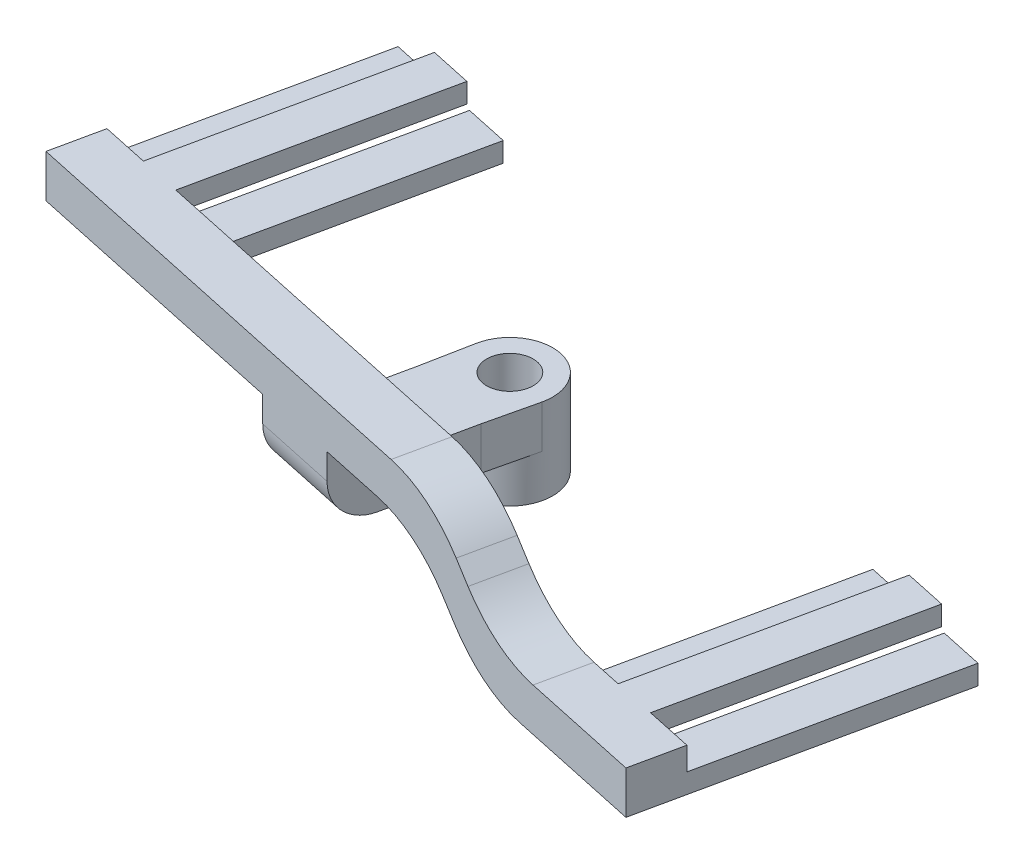
SolidWorks part; units mm, degrees
ref_plane "Front Plane" through (0, 0, 0) normal (0, 0, 1) x (1, 0, 0)
ref_plane "Top Plane" through (0, 0, 0) normal (0, 1, 0) x (1, 0, 0)
ref_plane "Right Plane" through (0, 0, 0) normal (1, 0, 0) x (0, 0, -1)
sketch "Sketch1" plane through (0, 0, 0) normal (0, 1, 0) x (1, 0, 0)
  circle A0 centre (0, 0) radius 3.175
  dimension "D1" = 6.35
extrude "Boss-Extrude1" add sketch "Sketch1" along normal blind 8.89
hole_wizard "#4 Clearance Hole1" positions "Sketch3" profile "Sketch2" hole size "#4" standard "ANSI Inch" end condition through all
sketch "Sketch3" plane through (0, 8.89, 0) normal (0, 1, 0) x (1, 0, 0)
  point P0 (0, 0)
sketch "Sketch2" plane through (0, 8.89, 0) normal (1, 0, 0) x (0, 0, 1)
  line L0 (0, 0) -> (0, 8.89)
  line L1 (0, 8.89) -> (1.7272, 8.89)
  line L2 (1.7272, 8.89) -> (1.7272, 0)
  line L5 (1.7272, 0) -> (0, 0)
  line L11 (0, -6.35) -> (0, 107.95) construction
  dimension "Thru Hole Dia." = 3.4544
  dimension "Thru Hole Depth" = 8.89
sketch "Sketch4" plane through (0, 8.89, 0) normal (0, 1, 0) x (1, 0, 0)
  line L0 (-32.7152, 14.478) -> (-32.7152, -1.524) construction
  line L1 (-1.7272, 1.7272) -> (-1.7272, -1.7272) construction
  line L2 (1.7272, 1.7272) -> (1.7272, -1.7272) construction
  line L3 (-1.7272, -1.7272) -> (1.7272, -1.7272) construction
  line L4 (-1.7272, 1.7272) -> (1.7272, 1.7272) construction
  line L5 (47.1932, -2.667) -> (47.1932, -18.669) construction
  line L6 (-32.7152, 14.478) -> (47.1932, -2.667) construction
  line L7 (47.1932, -18.669) -> (-32.7152, -1.524) construction
  circle A1 centre (0, 0) radius 1.7272 construction
  dimension "D2" = 45.466
  dimension "D1" = 30.988
  dimension "D3" = 16.002
  dimension "D4" = 16.002
  dimension "D5" = 2.667
  dimension "D6" = 1.524
sketch "Sketch5" plane through (0, 8.89, 0) normal (0, 1, 0) x (1, 0, 0)
  line L0 (8.5844, -15.5808) -> (-26.3256, -8.0906)
  line L1 (47.1932, -18.669) -> (-32.7152, -1.524) construction
  line L2 (-3.175, 0) -> (-3.175, -9.161)
  line L3 (-26.3256, -8.0906) -> (-21.7112, 13.4159)
  line L4 (3.175, 0) -> (3.175, -10.5234)
  line L5 (9.3837, -11.8556) -> (8.5844, -15.5808)
  line L7 (-15.5924, -6.4967) -> (-3.175, -9.161)
  line L8 (-21.7112, 13.4159) -> (-11.7773, 11.2845)
  line L9 (-11.7773, 11.2845) -> (-15.5924, -6.4967)
  line L10 (-32.7152, 14.478) -> (47.1932, -2.667) construction
  line L14 (9.3837, -11.8556) -> (3.175, -10.5234)
  circle A0 centre (0, 0) radius 3.175 construction
  arc A1 (-3.175, 0) -> (3.175, 0) centre (0, 0) ccw
  dimension "D1" = 3.81
  dimension "D2" = 1.27
  dimension "D3" = 12.7
  dimension "D4" = 10.16
  dimension "D5" = 1.27
  dimension "D8" = 6.35
extrude "Boss-Extrude2" add sketch "Sketch5" against normal blind 3.175
sketch "Sketch11" plane through (-2.8181, 0, 13.1343) normal (-0.2098, 0, 0.9777) x (0.9777, 0, 0.2098)
  line L0 (11.662, 8.89) -> (12.9771, 8.89)
  line L1 (-35.0245, 8.89) -> (46.7025, 8.89) construction
  line L2 (18.012, -0.635) -> (11.662, 5.715)
  line L3 (11.662, 5.715) -> (11.662, 8.89) construction
  line L4 (11.662, 8.89) -> (11.662, 5.715)
  line L5 (19.3271, 2.54) -> (21.822, 2.54)
  line L6 (12.9771, 8.89) -> (19.3271, 2.54)
  line L7 (18.012, -0.635) -> (21.822, -0.635)
  line L8 (11.662, 5.715) -> (-24.0425, 5.715) construction
  line L9 (21.822, 2.54) -> (21.822, -0.635)
  dimension "D1" = 3.175
  dimension "D2" = 6.35
  dimension "D3" = 3.175
  dimension "D4" = 45
  dimension "D5" = 3.81
extrude "Boss-Extrude3" add sketch "Sketch11" against normal up to surface (3.81 mm away) up to face at (6.2793, 7.3025, 11.1895)
sketch "Sketch12" plane through (0, 8.89, 0) normal (0, 1, 0) x (1, 0, 0)
  line L0 (18.5183, -17.7122) -> (23.1327, 3.7943)
  line L1 (23.1327, 3.7943) -> (33.0666, 1.6629)
  line L2 (33.0666, 1.6629) -> (28.4523, -19.8436)
  line L3 (28.4523, -19.8436) -> (18.5183, -17.7122)
  line L4 (-32.7152, 14.478) -> (47.1932, -2.667) construction
  dimension "D1" = 10.16
  dimension "D2" = 1.27
extrude "Boss-Extrude4" add sketch "Sketch12" against normal up to vertex from vertex
sketch "Sketch6" plane through (1.7963, 0, -8.3722) normal (0.2098, 0, -0.9777) x (-0.9777, 0, -0.2098)
  line L0 (24.0425, 7.3025) -> (13.8825, 7.3025) construction
  line L1 (-21.822, 0.9525) -> (-31.982, 0.9525) construction
  line L2 (13.8825, 5.715) -> (13.8825, 8.89) construction
  line L3 (17.2692, 5.715) -> (17.2692, 8.89) construction
  line L4 (24.0425, 5.715) -> (13.8825, 5.715) construction
  line L5 (20.6559, 8.89) -> (20.6559, 5.715) construction
  line L6 (24.0425, 8.89) -> (13.8825, 8.89) construction
  line L7 (-28.5953, -0.635) -> (-28.5953, 2.54) construction
  line L8 (13.8825, 5.715) -> (17.1422, 5.715)
  line L9 (13.8825, 5.715) -> (13.8825, 7.1755)
  line L10 (13.8825, 7.1755) -> (17.1422, 7.1755)
  line L11 (17.1422, 5.715) -> (17.1422, 7.1755)
  line L12 (17.3962, 8.89) -> (20.5289, 8.89)
  line L13 (17.3962, 8.89) -> (17.3962, 7.4295)
  line L14 (17.3962, 7.4295) -> (20.5289, 7.4295)
  line L15 (20.5289, 8.89) -> (20.5289, 7.4295)
  line L16 (24.0425, 5.715) -> (20.7829, 5.715)
  line L17 (24.0425, 7.1755) -> (24.0425, 5.715)
  line L18 (24.0425, 7.1755) -> (20.7829, 7.1755)
  line L19 (20.7829, 5.715) -> (20.7829, 7.1755)
  line L20 (13.8825, 8.89) -> (24.0425, 8.89)
  line L21 (13.8825, 8.89) -> (13.8825, 5.715)
  line L22 (13.8825, 5.715) -> (24.0425, 5.715)
  line L23 (24.0425, 8.89) -> (24.0425, 5.715)
  line L24 (24.0425, 5.715) -> (24.0425, 8.89) construction
  line L25 (-25.2087, 2.54) -> (-25.2087, -0.635) construction
  line L26 (-31.982, -0.635) -> (-28.7223, -0.635)
  line L27 (-31.982, -0.635) -> (-31.982, 0.8255)
  line L28 (-31.982, 0.8255) -> (-28.7223, 0.8255)
  line L29 (-28.7223, -0.635) -> (-28.7223, 0.8255)
  line L30 (-28.4683, 2.54) -> (-25.3357, 2.54)
  line L31 (-28.4683, 2.54) -> (-28.4683, 1.0795)
  line L32 (-28.4683, 1.0795) -> (-25.3357, 1.0795)
  line L33 (-25.3357, 2.54) -> (-25.3357, 1.0795)
  line L34 (-21.822, -0.635) -> (-25.0817, -0.635)
  line L35 (-21.822, 0.8255) -> (-21.822, -0.635)
  line L36 (-21.822, 0.8255) -> (-25.0817, 0.8255)
  line L37 (-25.0817, -0.635) -> (-25.0817, 0.8255)
  line L38 (-31.982, 2.54) -> (-21.822, 2.54)
  line L39 (-31.982, 2.54) -> (-31.982, -0.635)
  line L40 (-31.982, -0.635) -> (-21.822, -0.635)
  line L41 (-21.822, 2.54) -> (-21.822, -0.635)
  line L46 (-31.982, -0.635) -> (-21.822, -0.635) construction
  line L47 (-31.982, -0.635) -> (-31.982, 2.54) construction
  line L48 (-31.982, 2.54) -> (-21.822, 2.54) construction
  line L49 (-21.822, -0.635) -> (-21.822, 2.54) construction
  dimension "D1" = 3.3867
  dimension "D2" = 3.3867
  dimension "D3" = 0.254
  dimension "D4" = 0.127
  dimension "D5" = 0.127
  dimension "D6" = 0.127
  dimension "D7" = 0.127
  dimension "D8" = 0.254
  dimension "D9" = 0.127
  dimension "D10" = 0.127
  dimension "D11" = 0.127
  dimension "D12" = 0.127
  dimension "D13" = 3.3867
  dimension "D14" = 3.3867
extrude "Cut-Extrude1" cut sketch "Sketch6" against normal up to surface (18.1859 mm away)
sketch "Sketch13" plane through (0, 8.89, 0) normal (0, 1, 0) x (1, 0, 0)
  line L0 (-3.175, -9.161) -> (3.175, -10.5234)
  line L1 (3.175, -10.5234) -> (3.175, 7.2566)
  line L2 (3.175, 7.2566) -> (-3.175, 7.2566)
  line L3 (-3.175, 7.2566) -> (-3.175, -9.161)
  dimension "D1" = 17.78
extrude "Cut-Extrude2" cut sketch "Sketch13" against normal blind 5.08
sketch "Sketch14" plane through (-23.5075, 0, -5.0437) normal (-0.9777, 0, -0.2098) x (-0.2098, 0, 0.9777)
  line L0 (3.81, 0.635) -> (13.4332, 0.635)
  line L1 (3.81, 3.81) -> (3.81, 0.635)
  line L2 (13.4332, 5.715) -> (13.4332, -0.635) construction
  line L4 (13.4332, 0.635) -> (13.4332, 5.715)
  line L5 (13.4332, 5.715) -> (9.6355, 5.715)
  line L6 (13.4332, 5.715) -> (-8.5627, 5.715) construction
  line L7 (9.6232, 3.81) -> (3.81, 3.81)
  line L8 (3.175, 0.4927) -> (3.175, -0.5856) construction
  line L9 (3.175, 0) -> (3.175, 3.81) construction
  line L10 (9.6232, 5.715) -> (9.6232, -0.635) construction
  line L11 (9.6232, 5.715) -> (9.6232, 3.81)
  line L16 (9.6232, 5.715) -> (9.6355, 5.715)
  dimension "D1" = 0.635
  dimension "D3" = 3.175
extrude "Boss-Extrude5" add sketch "Sketch14" against normal up to vertex (27.1469 mm away) from vertex at -20.9382 starting at point (-3.175, 8.89, 0)
sketch "Sketch15" plane through (0, 3.81, 0) normal (0, 1, 0) x (1, 0, 0)
  line L0 (-3.8345, -3.074) -> (-3.1163, 0.6079)
  line L1 (2.236, -4.3765) -> (3.0914, -0.724)
  line L2 (-3.8345, -3.074) -> (2.236, -4.3765)
  arc A0 (-3.1163, 0.6079) -> (3.0914, -0.724) centre (0, 0) ccw
  circle A1 centre (0, 0) radius 3.175 construction
  circle M2 centre (0, 0) radius 3.175
extrude "Boss-Extrude6" add sketch "Sketch15" against normal up to surface (3.175 mm away) contours L0 L2 M2 | L2 L1 M2 up to face at (-1.8087, 0.635, 8.4298)
fillet "Fillet2" radius 8.89 4 edges at (8.9841, 5.715, 13.7182) (10.2699, 8.89, 13.9941) (16.4786, 2.54, 15.3262) (15.1928, -0.635, 15.0503)
fillet "Fillet3" radius 1.5875 1 edges at (-2.0188, 3.81, 9.4091)
fillet "Fillet4" radius 3.175 1 edges at (-2.8181, 0.635, 13.1343)
sketch "Sketch16" plane through (0, 0, 0) normal (0, -1, 0) x (1, 0, 0)
  circle A0 centre (0, 0) radius 1.7272
  circle A1 centre (0, 0) radius 3.175
  circle A2 centre (0, 0) radius 1.7272 construction
  circle A3 centre (0, 0) radius 3.175 construction
extrude "Boss-Extrude7" add sketch "Sketch16" along normal blind 2.54
